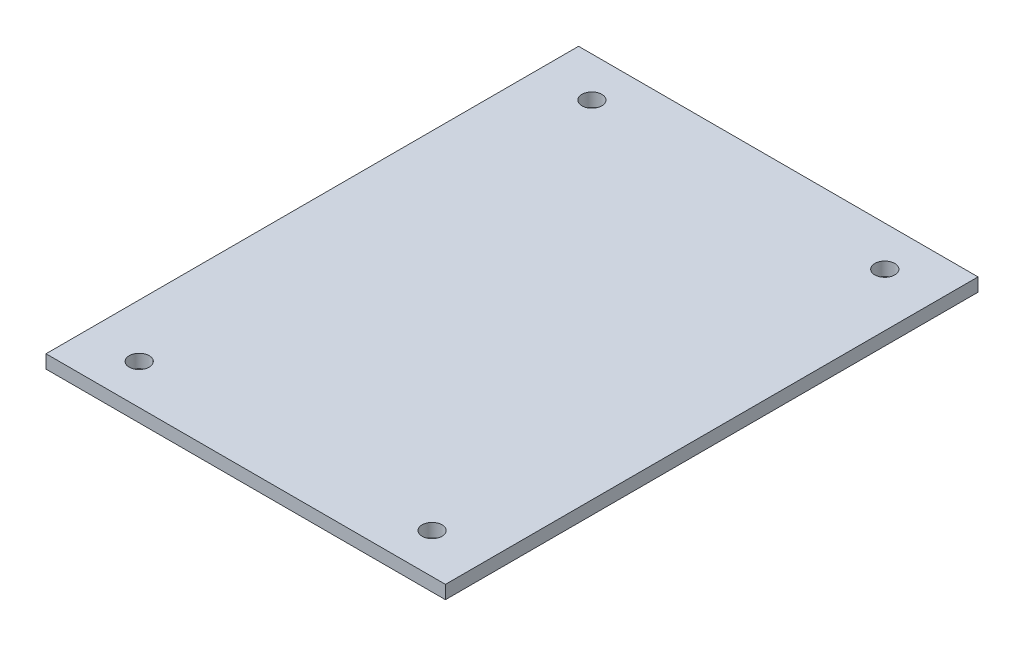
SolidWorks part; units mm, degrees
ref_plane "Front Plane" through (0, 0, 0) normal (0, 0, 1) x (1, 0, 0)
ref_plane "Top Plane" through (0, 0, 0) normal (0, 1, 0) x (1, 0, 0)
ref_plane "Right Plane" through (0, 0, 0) normal (1, 0, 0) x (0, 0, -1)
sketch "Sketch1" plane through (0, 0, 0) normal (0, 1, 0) x (1, 0, 0)
  line L1 (-38.1, 50.8) -> (38.1, 50.8)
  line L2 (-38.1, 50.8) -> (-38.1, -50.8)
  line L3 (-38.1, -50.8) -> (38.1, -50.8)
  line L4 (38.1, 50.8) -> (38.1, -50.8)
  line L5 (-38.1, 50.8) -> (38.1, -50.8) construction
  line L6 (-38.1, -50.8) -> (38.1, 50.8) construction
  point P0 (0, 0)
  dimension "D1" = 76.2
  dimension "D2" = 101.6
extrude "Boss-Extrude1" add sketch "Sketch1" along normal blind 2.54
sketch "Sketch2" plane through (0, 2.54, 0) normal (0, 1, 0) x (1, 0, 0)
  line L0 (0, 50.8) -> (0, -50.8) construction
  line L1 (38.1, 50.8) -> (-38.1, 50.8) construction
  line L2 (-38.1, -50.8) -> (38.1, -50.8) construction
  line L3 (-38.1, 0) -> (38.1, 0) construction
  line L4 (-38.1, 50.8) -> (-38.1, -50.8) construction
  line L5 (38.1, -50.8) -> (38.1, 50.8) construction
  circle A0 centre (-27.94, 43.18) radius 1.905
  circle A1 centre (27.94, 43.18) radius 1.905
  circle A2 centre (-27.94, -43.18) radius 1.905
  circle A3 centre (27.94, -43.18) radius 1.905
  point P20 (0, 0)
  dimension "D1" = 55.88
  dimension "D7" = 3.81
  dimension "D8" = 3.81
  dimension "D9" = 3.81
  dimension "D10" = 3.81
  dimension "D2" = 86.36
  dimension "D3" = 86.36
  dimension "D4" = 55.88
  dimension "D5" = 43.18
  dimension "D6" = 10.16
extrude "Cut-Extrude1" cut sketch "Sketch2" against normal through all
